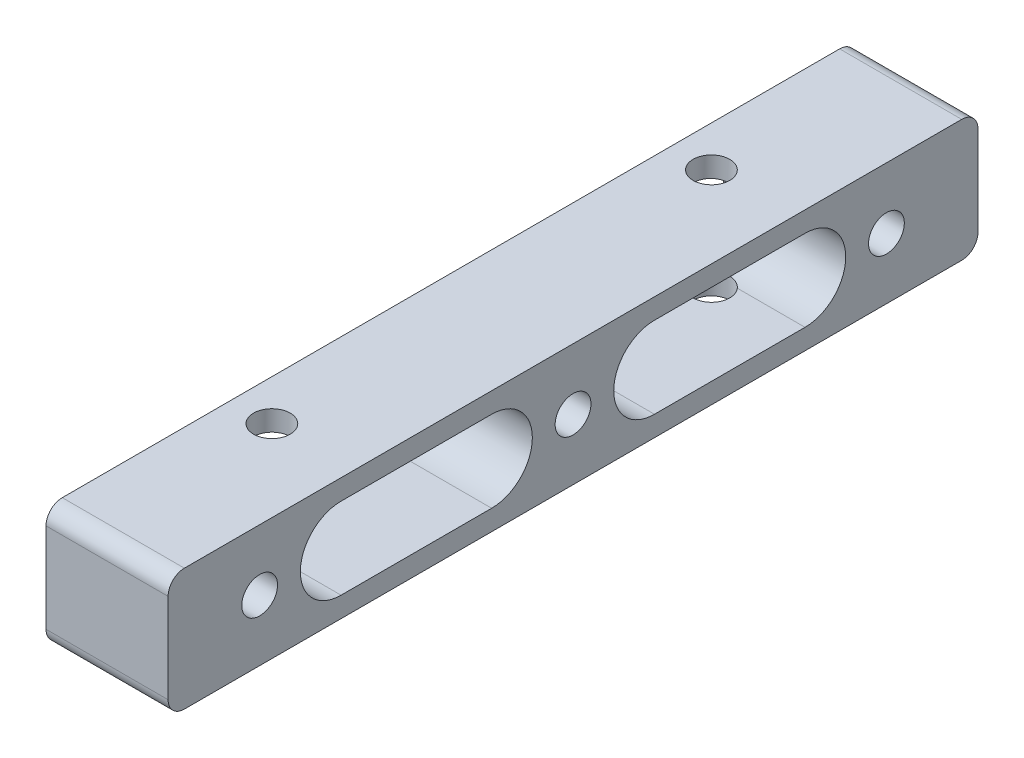
SolidWorks part; units mm, degrees
ref_plane "前视基准面" through (0, 0, 0) normal (0, 0, 1) x (1, 0, 0)
ref_plane "上视基准面" through (0, 0, 0) normal (0, 1, 0) x (1, 0, 0)
ref_plane "右视基准面" through (0, 0, 0) normal (1, 0, 0) x (0, 0, -1)
other "Configuration Table"
sketch "草图1" plane through (0, 0, 0) normal (1, 0, 0) x (0, 0, -1)
  line L1 (0, 0) -> (99.5, 0)
  line L2 (0, 0) -> (0, -15)
  line L3 (0, -15) -> (99.5, -15)
  line L4 (99.5, 0) -> (99.5, -15)
  dimension "D1" = 99.5
  dimension "D2" = 15
extrude "凸台-拉伸1" add sketch "草图1" along normal blind 15
sketch "草图2" plane through (15, 0, 0) normal (1, 0, 0) x (0, 0, -1)
  line L0 (0, -7.5) -> (99.5, -7.5) construction
  line L3 (49.75, 0) -> (49.75, -15) construction
  line L4 (99.5, 0) -> (0, 0) construction
  line L5 (0, -15) -> (99.5, -15) construction
  line L6 (0, 0) -> (0, -15) construction
  line L7 (99.5, -15) -> (99.5, 0) construction
  circle A0 centre (49.75, -7.5) radius 2.2
  circle A1 centre (11.25, -7.5) radius 2.2
  circle A2 centre (88.25, -7.5) radius 2.2
  dimension "D1" = 4.4
  dimension "D2" = 77
extrude "切除-拉伸1" cut sketch "草图2" against normal blind 55
sketch "草图3" plane through (15, 0, 0) normal (1, 0, 0) x (0, 0, -1)
  line L0 (0, -7.5) -> (99.5, -7.5) construction
  line L1 (0, 0) -> (0, -15) construction
  line L2 (99.5, -15) -> (99.5, 0) construction
  line L3 (21.25, -7.5) -> (39.75, -7.5) construction
  line L4 (21.25, -2.5) -> (39.75, -2.5)
  line L5 (21.25, -12.5) -> (39.75, -12.5)
  line L6 (59.75, -7.5) -> (78.25, -7.5) construction
  line L7 (0, 0) -> (0, -15)
  line L8 (0, -15) -> (99.5, -15)
  line L9 (99.5, -15) -> (99.5, 0)
  line L10 (99.5, 0) -> (0, 0)
  line L11 (0, 0) -> (0, -15)
  line L12 (0, -15) -> (99.5, -15)
  line L13 (99.5, -15) -> (99.5, 0)
  line L14 (99.5, 0) -> (0, 0)
  line L15 (59.75, -2.5) -> (78.25, -2.5)
  line L16 (59.75, -12.5) -> (78.25, -12.5)
  line L17 (49.75, 0) -> (49.75, -15) construction
  arc A0 (21.25, -2.5) -> (21.25, -12.5) centre (21.25, -7.5) ccw
  arc A1 (39.75, -12.5) -> (39.75, -2.5) centre (39.75, -7.5) ccw
  arc A2 (59.75, -2.5) -> (59.75, -12.5) centre (59.75, -7.5) ccw
  arc A3 (78.25, -12.5) -> (78.25, -2.5) centre (78.25, -7.5) ccw
  circle A4 centre (11.25, -7.5) radius 2.2 construction
  circle A5 centre (11.25, -7.5) radius 2.2
  circle A6 centre (49.75, -7.5) radius 2.2 construction
  circle A7 centre (49.75, -7.5) radius 2.2
  point P12 (30.5, -7.5)
  point P17 (69, -7.5)
  dimension "D2" = 10
  dimension "D4" = 5
  dimension "D1" = 0
  dimension "D3" = 10
extrude "切除-拉伸2" cut sketch "草图3" against normal blind 48 contours L5 A0 L4 A1 | L16 A3 L15 A2
fillet "圆角1" radius 2 4 edges at (7.5, -15, -99.5) (7.5, 0, -99.5) (7.5, -15, 0) (7.5, 0, 0)
sketch "草图4" plane through (0, 0, 0) normal (0, 1, 0) x (1, 0, 0)
  line L0 (0, 49.75) -> (15, 49.75) construction
  line L1 (5, 97.5) -> (5, 2)
  line L4 (15, 2) -> (15, 97.5)
  line L5 (15, 97.5) -> (0, 97.5)
  line L6 (0, 97.5) -> (0, 2)
  line L7 (0, 2) -> (15, 2)
  line L8 (15, 2) -> (15, 97.5)
  line L9 (15, 97.5) -> (0, 97.5)
  line L10 (0, 97.5) -> (0, 2)
  line L11 (0, 2) -> (15, 2)
  circle A0 centre (5, 76.75) radius 2.25
  circle A1 centre (5, 22.75) radius 2.25
  point P11 (5, 97.5)
  point P13 (5, 2)
  dimension "D2" = 54
  dimension "D3" = 4.5
  dimension "D4" = 5
  dimension "D1" = 0
extrude "切除-拉伸3" cut sketch "草图4" against normal blind 31 contours L1 A1 | L1 A1 | L1 A0 | L1 A0
